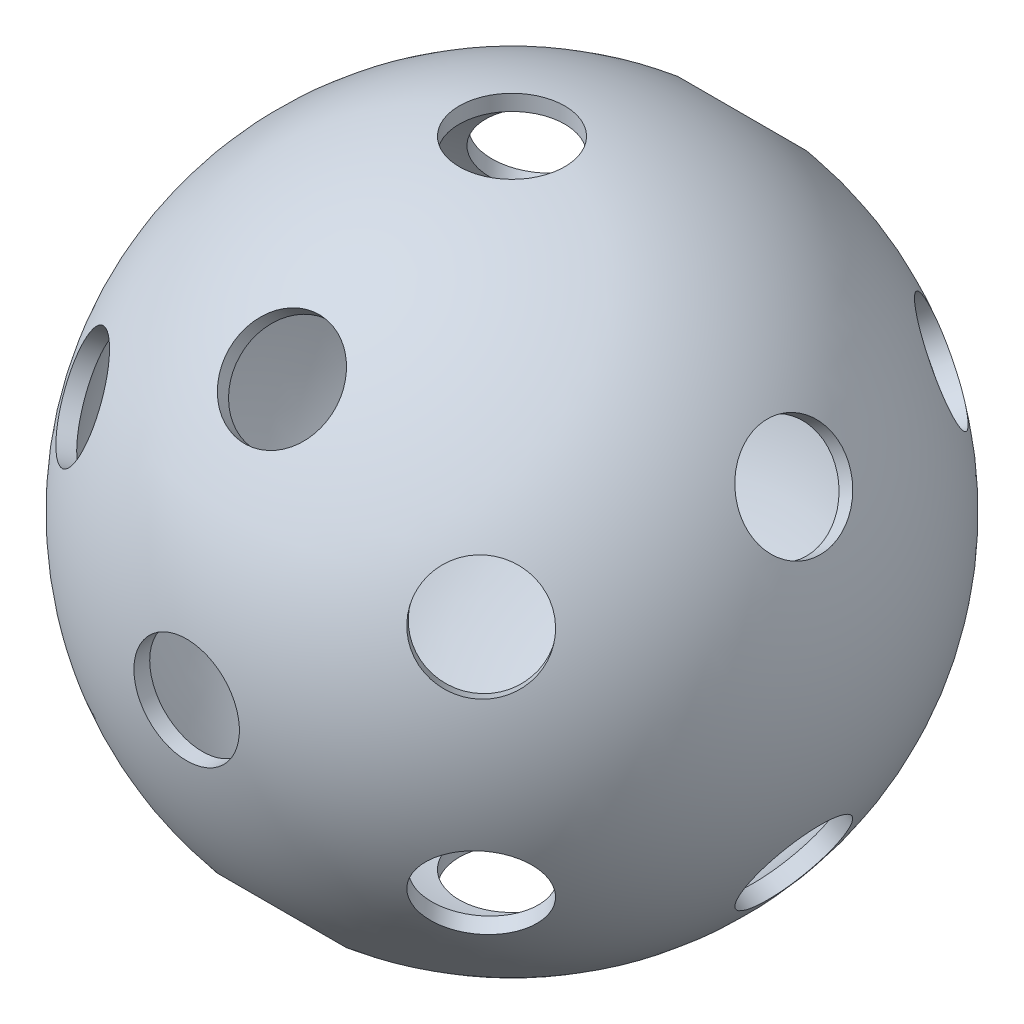
SolidWorks part; units mm, degrees
material "ABS"
ref_plane "Front Plane" through (0, 0, 0) normal (0, 0, 1) x (1, 0, 0)
ref_plane "Top Plane" through (0, 0, 0) normal (0, 1, 0) x (1, 0, 0)
ref_plane "Right Plane" through (0, 0, 0) normal (1, 0, 0) x (0, 0, -1)
sketch "Sketch1" plane through (0, 0, 0) normal (0, 0, 1) x (1, 0, 0)
  line L0 (0, 63.5) -> (0, -63.5) construction
  arc A0 (0, 63.5) -> (0, -63.5) centre (0, 0) cw
  point P8 (0, 0)
  dimension "D1" = 127
revolve "Revolve-Thin1" add sketch "Sketch1" angle 360 about L0
sketch "Sketch2" plane through (0, 0, 0) normal (0, 0, 1) x (1, 0, 0)
  line L4 (0, 0) -> (-63.5, 0) construction
  circle A0 centre (0, 0) radius 10.16
  circle A4 centre (0, 0) radius 63.5 construction
  dimension "D1" = 20.32
  dimension "D3" = 63.5
extrude "Cut-Extrude1" cut sketch "Sketch2" along normal through all contours A0
sketch "Sketch8" plane through (0, 0, 0) normal (0, 1, 0) x (1, 0, 0)
  line L0 (0, 0) -> (0, 63.5)
  line L1 (0, 0) -> (-63.5, 0)
  circle A0 centre (0, 0) radius 63.5 construction
pattern_circular "CirPattern29" count 8 over 360 about axis through (0, 0, 0) along (-1, 0, 0) of "Cut-Extrude1"
pattern_circular "CirPattern30" count 6 over 360 about axis through (0, 0, 0) along (0, 0, -1) of "CirPattern29"
